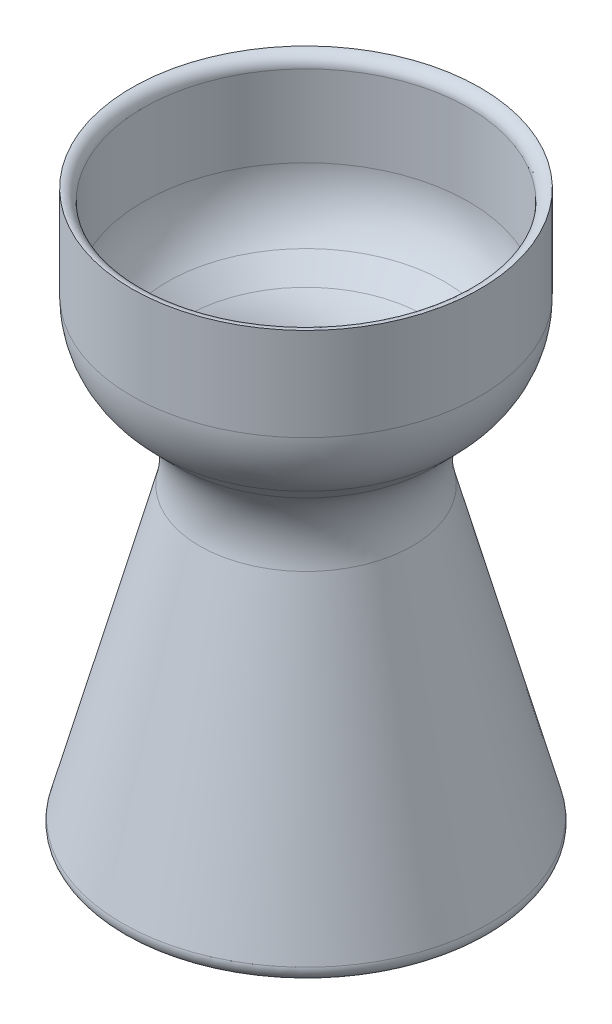
SolidWorks part; units mm, degrees
ref_plane "Front Plane" through (0, 0, 0) normal (0, 0, 1) x (1, 0, 0)
ref_plane "Top Plane" through (0, 0, 0) normal (0, 1, 0) x (1, 0, 0)
ref_plane "Right Plane" through (0, 0, 0) normal (1, 0, 0) x (0, 0, -1)
sketch "Sketch1" plane through (0, 0, 0) normal (0, 0, 1) x (1, 0, 0)
  line L0 (47.9298, 0) -> (25.9988, 81.8477)
  line L1 (34.8179, 104.1371) -> (40.1855, 109.5048)
  line L4 (37.9404, 111.7498) -> (32.5728, 106.3822)
  line L5 (29.0656, 82.6694) -> (50.1749, 3.8886)
  line L6 (0, 0) -> (0, 152.8653) construction
  line L7 (47.625, 127.4653) -> (47.625, 152.8653)
  line L8 (44.45, 149.6903) -> (44.45, 127.4653)
  arc A5 (50.1749, 3.8886) -> (47.9298, 0) centre (47.108, 3.0668) cw
  arc A6 (25.9988, 81.8477) -> (32.5728, 106.3822) centre (50.5333, 88.4217) cw
  arc A7 (29.0656, 82.6694) -> (34.8179, 104.1371) centre (50.5333, 88.4217) cw
  arc A8 (47.625, 152.8653) -> (44.45, 149.6903) centre (47.625, 149.6903) ccw
  arc A9 (44.45, 127.4653) -> (37.9404, 111.7498) centre (22.225, 127.4653) cw
  arc A10 (47.625, 127.4653) -> (40.1855, 109.5048) centre (22.225, 127.4653) cw
  point P12 (47.625, 140.1653)
  point P13 (25.1333, 88.4217)
  point P21 (0, 0)
  point P22 (65.5855, 420.6632)
  point P23 (0, 0)
  point P24 (0, 0)
  point P25 (25.9988, 499.4822)
  point P26 (25.9988, 316.8569)
  point P27 (25.9988, 203.2065)
  point P28 (28.3083, 278.0264)
  dimension "D2" = 45
  dimension "D6" = 25.4
  dimension "D7" = 25.4
  dimension "D1" = 47.625
  dimension "D3" = 15
  dimension "D4" = 3.175
  dimension "D5" = 25.1333
  dimension "D8" = 25.4
  dimension "D9" = 47.9298
revolve "Revolve1" add sketch "Sketch1" angle 360 about L6
